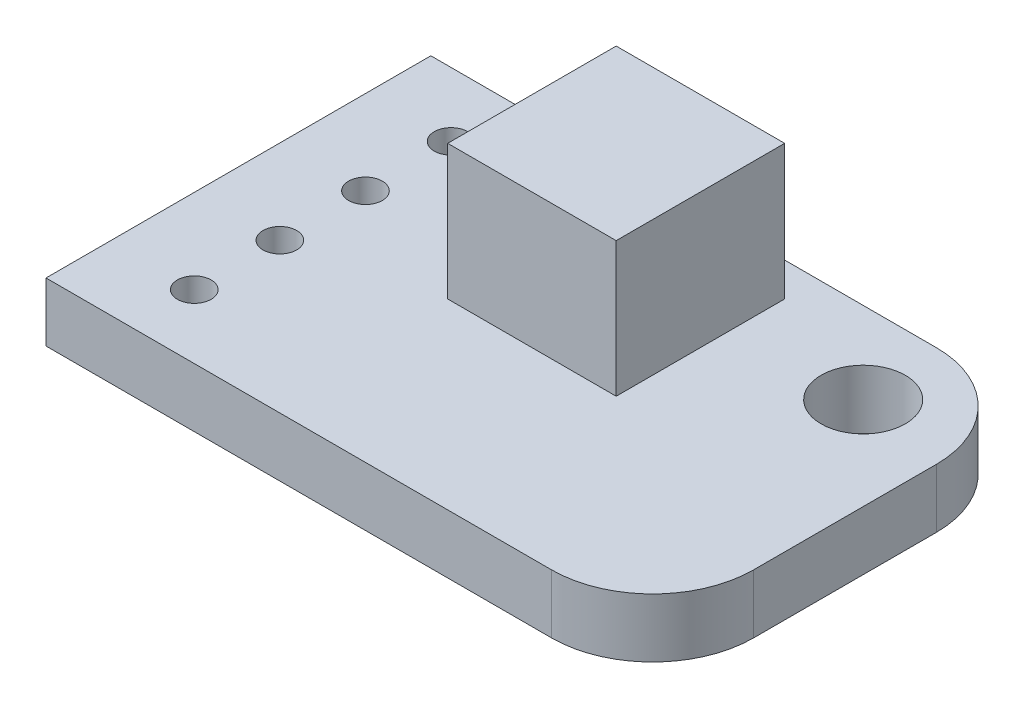
SolidWorks part; units mm, degrees
ref_plane "Front Plane" through (0, 0, 0) normal (0, 0, 1) x (1, 0, 0)
ref_plane "Top Plane" through (0, 0, 0) normal (0, 1, 0) x (1, 0, 0)
ref_plane "Right Plane" through (0, 0, 0) normal (1, 0, 0) x (0, 0, -1)
sketch "Sketch1" plane through (0, 0, 0) normal (0, 1, 0) x (1, 0, 0)
  line L0 (-5, -3.81) -> (-5, -1.27) construction
  line L1 (-7.5, 5.71) -> (7.5, 5.71)
  line L2 (-7.5, 5.71) -> (-7.5, -5.71)
  line L3 (-7.5, -5.71) -> (7.5, -5.71)
  line L4 (10.5, 2.71) -> (10.5, -2.71)
  line L5 (-5, -1.27) -> (-5, 1.27) construction
  line L6 (-5, 1.27) -> (-5, 3.81) construction
  circle A0 centre (7.75, 3.29) radius 1.25
  arc A1 (10.5, -2.71) -> (7.5, -5.71) centre (7.5, -2.71) cw
  arc A2 (7.5, 5.71) -> (10.5, 2.71) centre (7.5, 2.71) cw
  circle A3 centre (-5, 3.81) radius 0.5
  circle A4 centre (-5, 1.27) radius 0.5
  circle A5 centre (-5, -1.27) radius 0.5
  circle A6 centre (-5, -3.81) radius 0.5
  point P4 (0, 5.71)
  point P6 (10.5, 0)
  point P13 (10.5, 5.71)
  point P22 (-5, 0)
  point P23 (-7.5, 0)
  dimension "D3" = 2.5
  dimension "D6" = 3
  dimension "D7" = 1
  dimension "D1" = 18
  dimension "D2" = 11.42
  dimension "D4" = 9
  dimension "D5" = 15.25
  dimension "D8" = 2.5
  dimension "D9" = 2.54
extrude "Boss-Extrude1" add sketch "Sketch1" along normal mid plane 1.75
sketch "Sketch2" plane through (0, 0.875, 0) normal (0, 1, 0) x (1, 0, 0)
  line L0 (-7.5, 5.71) -> (-7.5, -5.71) construction
  line L1 (-1, 4.71) -> (4, 4.71)
  line L2 (-1, 4.71) -> (-1, -0.29)
  line L3 (-1, -0.29) -> (4, -0.29)
  line L4 (4, 4.71) -> (4, -0.29)
  line L5 (7.5, 5.71) -> (-7.5, 5.71) construction
  point P4 (1.5, 4.71)
  point P7 (4, 2.21)
  dimension "D1" = 5
  dimension "D2" = 5
  dimension "D3" = 9
  dimension "D4" = 3.5
extrude "Boss-Extrude2" add sketch "Sketch2" along normal blind 4
